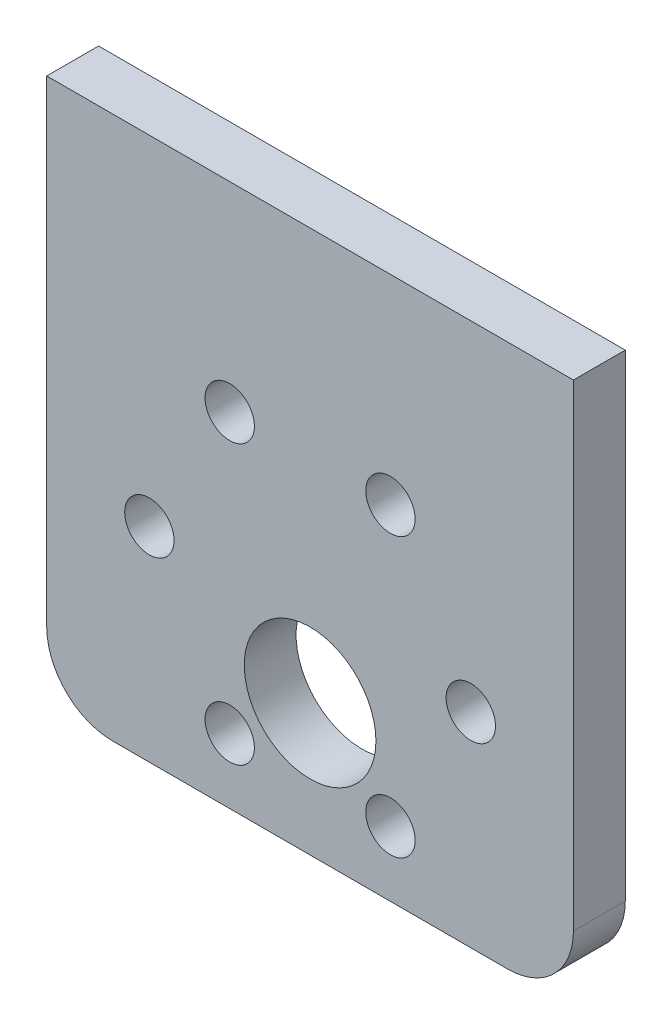
SolidWorks part; units mm, degrees
material "Oak"
ref_plane "Front Plane" through (0, 0, 0) normal (0, 0, 1) x (1, 0, 0)
ref_plane "Top Plane" through (0, 0, 0) normal (0, 1, 0) x (1, 0, 0)
ref_plane "Right Plane" through (0, 0, 0) normal (1, 0, 0) x (0, 0, -1)
sketch "Sketch1" plane through (0, 0, 0) normal (0, 0, 1) x (1, 0, 0)
  line L1 (-25.4, -26.1874) -> (25.4, -26.1874)
  line L2 (-25.4, -26.1874) -> (-25.4, 26.1874)
  line L3 (-25.4, 26.1874) -> (25.4, 26.1874)
  line L4 (25.4, -26.1874) -> (25.4, 26.1874)
  line L5 (-25.4, -26.1874) -> (25.4, 26.1874) construction
  line L6 (-25.4, 26.1874) -> (25.4, -26.1874) construction
  point P0 (0, 0)
  dimension "D1" = 52.3748
  dimension "D2" = 50.8
extrude "Boss-Extrude1" add sketch "Sketch1" along normal mid plane 5
hole_wizard "1/2 (0.5) Diameter Hole1" positions "Sketch2" profile "Sketch3" hole size "1/2" standard "ANSI Inch" end condition through all
sketch "Sketch2" plane through (0, 0, 2.5) normal (0, 0, 1) x (1, 0, 0)
  line L0 (-25.4, -26.1874) -> (25.4, -26.1874) construction
  point P8 (0, -13.4874)
  dimension "D1" = 12.7
sketch "Sketch3" plane through (0, -13.4874, 2.5) normal (1, 0, 0) x (0, -1, 0)
  line L0 (0, 0) -> (0, 5)
  line L1 (0, 5) -> (6.35, 5)
  line L2 (6.35, 5) -> (6.35, 0)
  line L5 (6.35, 0) -> (0, 0)
  line L11 (0, -6.35) -> (0, 107.95) construction
  dimension "Thru Hole Dia." = 12.7
  dimension "Thru Hole Depth" = 5
hole_wizard "3/16 (0.1875) Diameter Hole1" positions "Sketch4" profile "Sketch5" hole size "3/16" standard "ANSI Inch" end condition through all
sketch "Sketch4" plane through (0, 0, -2.5) normal (0, 0, -1) x (-1, 0, 0)
  point P17 (15.5, -6.4874)
  point P20 (7.75, 6.936)
  point P23 (-7.75, 6.936)
  point P26 (-15.5, -6.4874)
  point P31 (7.75, -19.9108)
  point P34 (-7.75, -19.9108)
sketch "Sketch5" plane through (-15.5, -6.4874, -2.5) normal (1, 0, 0) x (0, 1, 0)
  line L0 (0, 0) -> (0, 5)
  line L1 (0, 5) -> (2.3812, 5)
  line L2 (2.3812, 5) -> (2.3812, 0)
  line L5 (2.3812, 0) -> (0, 0)
  line L11 (0, -6.35) -> (0, 107.95) construction
  dimension "Thru Hole Dia." = 4.7625
  dimension "Thru Hole Depth" = 5
fillet "Fillet1" radius 6.35 2 edges at (25.4, -26.1874, 0) (-25.4, -26.1874, 0)
